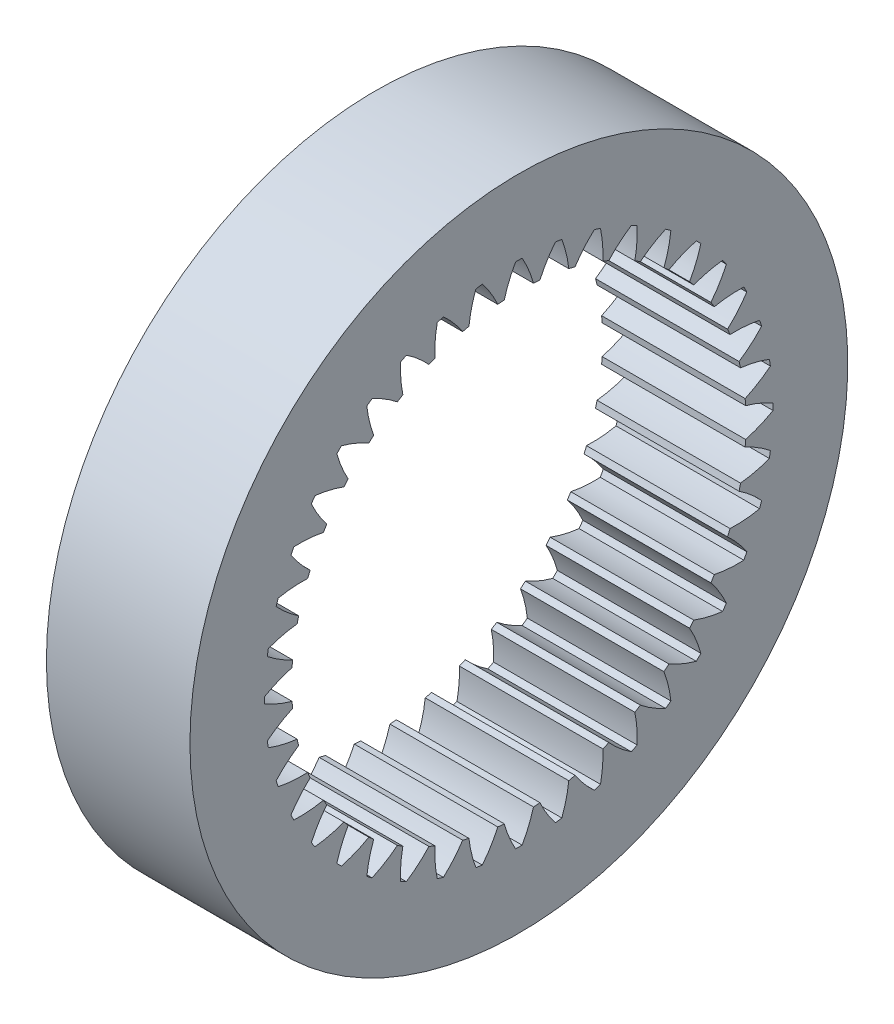
SolidWorks part; units mm, degrees
ref_plane "Plane1" through (0, 0, 0) normal (0, 0, 1) x (1, 0, 0)
ref_plane "Plane2" through (0, 0, 0) normal (0, 1, 0) x (1, 0, 0)
ref_plane "Plane3" through (0, 0, 0) normal (1, 0, 0) x (0, 0, -1)
other "Configuration Table"
sketch "HoldingSke" plane through (0, 0, 0) normal (0, 1, 0) x (1, 0, 0)
  line L0 (0, 0) -> (0.766, -0.6428)
  line L1 (-15, 0) -> (100, 0) construction
  line L2 (0, 0) -> (-2.1039, 2.3779)
  line L3 (0, 0) -> (-11.863, 4.5341)
  line L4 (0, 0) -> (6.6156, 5.5511)
  line L5 (0, 0) -> (-23.7986, -8.8762)
  line L6 (0, 0) -> (-10.5278, -7.1032)
  line L7 (-2.1039, 2.3779) -> (3.3635, 27.1825)
  line L8 (-76.2, 3.3779) -> (-54.61, 3.3779)
  line L9 (-71.009, 38.7566) -> (-53.1078, 45.2721)
  line L10 (-76.2, 71.12) -> (104.1128, 71.12)
  line L11 (0, 0) -> (-12, 0)
  line L12 (-76.2, 101.6) -> (-76.162, 101.6)
  line L13 (24.9733, 27.94) -> (52.9518, 28.4284)
  line L14 (24.9733, 27.94) -> (24.9743, 27.94)
  line L15 (24.9733, 27.94) -> (100.4006, 29.5858)
  circle A0 centre (0, 0) radius 27.5
  circle A1 centre (0, 0) radius 12.7
  circle A2 centre (0, 0) radius 12.7
  dimension "MHD" = 25.4
  dimension "Hub_dia" = 25.4
  dimension "Diameter" = 55
  dimension "Num_teeth" = 40
  dimension "Pitch" = 1
  dimension "Overall_len" = 25.4
  dimension "Show_teeth" = 40
  dimension "Thickness" = 12.7
  dimension "OAL" = 25.4001
  dimension "T_dim" = 21.59
  dimension "Ap" = 20
  dimension "H" = 19.05
  dimension "Pitch_radius" = 180.3128
  dimension "Width" = 12
  dimension "Backlash" = 0.038
  dimension "Addendum_fac" = 1
  dimension "Dedendum_fac" = 1.25
  dimension "Clearance_fac" = 0.25
  dimension "Dedendum_add" = 0.001
  dimension "Module" = 1
sketch "BasProSke" plane through (0, 0, 0) normal (0, 1, 0) x (1, 0, 0)
  line L0 (-10, 0) -> (60, 0) construction
  line L1 (0, 19) -> (0, 27.5)
  line L2 (0, 19) -> (12, 19)
  line L3 (12, 19) -> (12, 27.5)
  line L4 (12, 27.5) -> (0, 27.5)
  dimension "Diameter" = 55
  dimension "Thickness" = 12
  dimension "Inside_diameter" = 38
revolve "Base-Revolve" add sketch "BasProSke" angle 360 about L0
sketch "TooCutSke" plane through (0, 0, 0) normal (1, 0, 0) x (0, 0, -1)
  line L3 (0.8802, 19.9806) -> (0.8802, 53.6633) construction
  line L4 (0, 0) -> (0, 59.563) construction
  line L5 (0, 0) -> (-5.3609, 68.1169) construction
  line L6 (-8.4195, 16.3041) -> (36.3991, 19.8314) construction
  circle A0 centre (0, 0) radius 20 construction
  circle A1 centre (0, 0) radius 21.251 construction
  circle A2 centre (0, 0) radius 16.9145 construction
  circle A3 centre (0, 0) radius 18.9746 construction
  arc A4 (1.2283, 18.9348) -> (0.2723, 21.2493) centre (-8.4195, 16.3041) ccw
  arc A5 (1.2283, 18.9348) -> (-1.2283, 18.9348) centre (0, 0) ccw
  arc A6 (0.2723, 21.2493) -> (-0.2723, 21.2493) centre (0, 0) ccw
  arc A7 (-0.2723, 21.2493) -> (-1.2283, 18.9348) centre (8.4195, 16.3041) ccw
  dimension "Pitch_dia" = 40
  dimension "Base_dia" = 33.8289
  dimension "Root_dia" = 42.502
  dimension "Overcut_dia" = 37.9492
  dimension "Flank_rad" = 10
  dimension "Half_ang" = 4.5
  dimension "Half_CT" = 0.8802
extrude "ToothCut" cut sketch "TooCutSke" along normal through all
fillet "Breaks" [suppressed] radius 0.1
fillet "RootFillets" [suppressed] radius 0.251
pattern_circular "TeethCuts" count 40 every 9 about axis through (-10, 0, 0) along (1, 0, 0) of "RootFillets", "Breaks", "ToothCut"
equation "' \"Module@HoldingSke\" = 6.35"
equation "' \"Num_teeth@HoldingSke\" = 24"
equation "' \"Ap@HoldingSke\" =  14.5"
equation "' \"Ap@HoldingSke\" = 14.5"
equation "' \"Width@HoldingSke\" = 12"
equation "' \"Diameter@HoldingSke\" = 8 * 25.4"
equation "' \"Show_teeth@HoldingSke\" = 100"
equation "' \"Backlash@HoldingSke\" = 0.009 * 25.4"
equation "' \"Addendum_fac@HoldingSke\" = 1.0"
equation "' \"Dedendum_fac@HoldingSke\" = 1.25"
equation "' \"Dedendum_add@HoldingSke\" = 0.00005 * 25.4"
equation "' \"Clearance_fac@HoldingSke\" = 0.25"
equation "\"Pitch@HoldingSke\" = 1 / \"Module@HoldingSke\" "
equation "\"Overcut_dia@TooCutSke\" = (\"Num_teeth@HoldingSke\" - 2 * \"Addendum_fac@HoldingSke\") / \"Pitch@HoldingSke\" - 0.002 * 25.4"
equation "\"Pitch_dia@TooCutSke\" = \"Num_teeth@HoldingSke\" / \"Pitch@HoldingSke\""
equation "\"Base_dia@TooCutSke\" = \"Num_teeth@HoldingSke\" / \"Pitch@HoldingSke\" * cos((\"Ap@HoldingSke\"  * 3.14159265 / 180)) * 0.90"
equation "\"Root_dia@TooCutSke\" = \"Num_teeth@HoldingSke\"  / \"Pitch@HoldingSke\" + 2 *  \"Dedendum_fac@HoldingSke\"/ \"Pitch@HoldingSke\" + \"Dedendum_add@HoldingSke\" * 2"
equation "\"Half_ang@TooCutSke\" = 180 / \"Num_teeth@HoldingSke\""
equation "\"Half_CT@TooCutSke\" = \"Num_teeth@HoldingSke\" / \"Pitch@HoldingSke\" * sin((3.14159265 / 2 / \"Num_teeth@HoldingSke\")) / 2 + 10 * \"Backlash@HoldingSke\" / 4"
equation "\"Flank_rad@TooCutSke\" = \"Num_teeth@HoldingSke\" / \"Pitch@HoldingSke\" / 4"
equation "\"Radius@RootFillets\"= \"Clearance_fac@HoldingSke\" / \"Pitch@HoldingSke\" + \"Dedendum_add@HoldingSke\""
equation "\"Break_rad@Breaks\" = 0.02 / \"Pitch@HoldingSke\" * 5"
equation "\"Num_teeth@TeethCuts\" = int( \"Show_teeth@HoldingSke\" ) + 1"
equation "\"Num_teeth@TeethCuts\" = ((sgn( \"Num_teeth@TeethCuts\" - \"Num_teeth@HoldingSke\" )-1)*( \"Num_teeth@TeethCuts\" - \"Num_teeth@HoldingSke\" ))/-2+ \"Num_teeth@HoldingSke\""
equation "\"Num_teeth@TeethCuts\" = ((sgn( \"Num_teeth@TeethCuts\" - 2.0)+1)*( \"Num_teeth@TeethCuts\" - 2.0))/2 +2.0"
equation "\"Angle@TeethCuts\" = 360.0 / \"Num_teeth@HoldingSke\""
equation "\"Diameter@BasProSke\" = \"Num_teeth@HoldingSke\"  / \"Pitch@HoldingSke\" + 2 *  \"Dedendum_fac@HoldingSke\"/ \"Pitch@HoldingSke\" + \"Dedendum_add@HoldingSke\" * 2 + 0.002 * 25.4"
equation "\"Diameter@BasProSke\" = ((sgn( \"Diameter@BasProSke\"  - \"Diameter@HoldingSke\" )+1)*( \"Diameter@BasProSke\"  - \"Diameter@HoldingSke\" ))/2 + \"Diameter@HoldingSke\""
equation "\"Inside_diameter@BasProSke\" =  (\"Num_teeth@HoldingSke\" - 2 * \"Addendum_fac@HoldingSke\") / \"Pitch@HoldingSke\" "
equation "\"Thickness@BasProSke\"  = \"Width@HoldingSke\""
